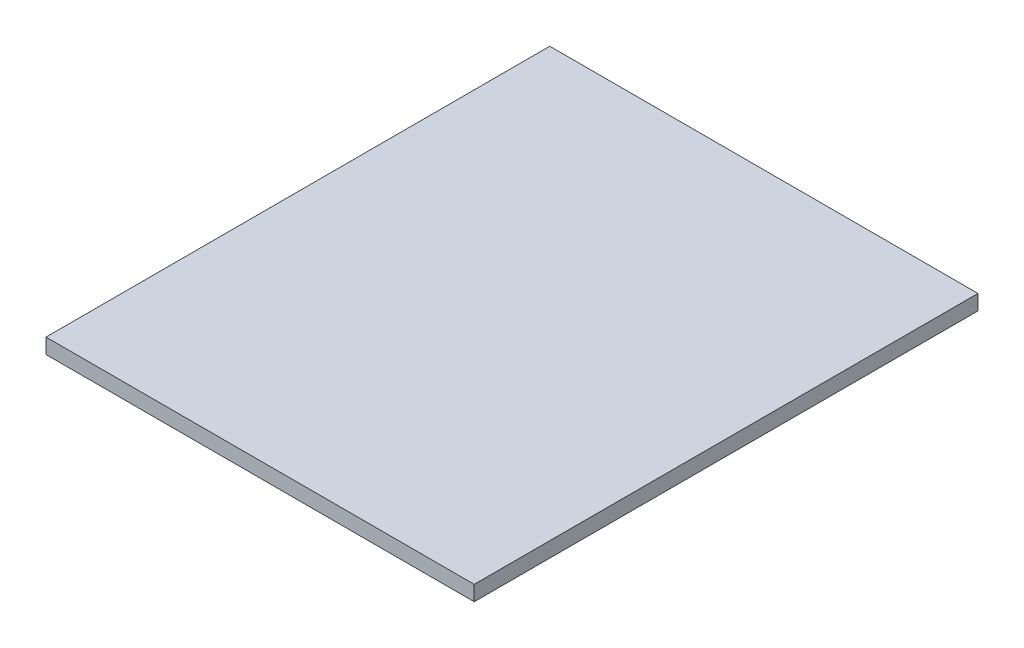
SolidWorks part; units mm, degrees
ref_plane "Спереди" through (0, 0, 0) normal (0, 0, 1) x (1, 0, 0)
ref_plane "Сверху" through (0, 0, 0) normal (0, 1, 0) x (1, 0, 0)
ref_plane "Справа" through (0, 0, 0) normal (1, 0, 0) x (0, 0, -1)
sketch "Эскиз1" plane through (0, 0, 0) normal (0, 1, 0) x (1, 0, 0)
  line L1 (0, 100) -> (85, 100)
  line L2 (0, 100) -> (0, 0)
  line L3 (0, 0) -> (85, 0)
  line L4 (85, 100) -> (85, 0)
extrude "Бобышка-Вытянуть1" add sketch "Эскиз1" along normal blind 3
